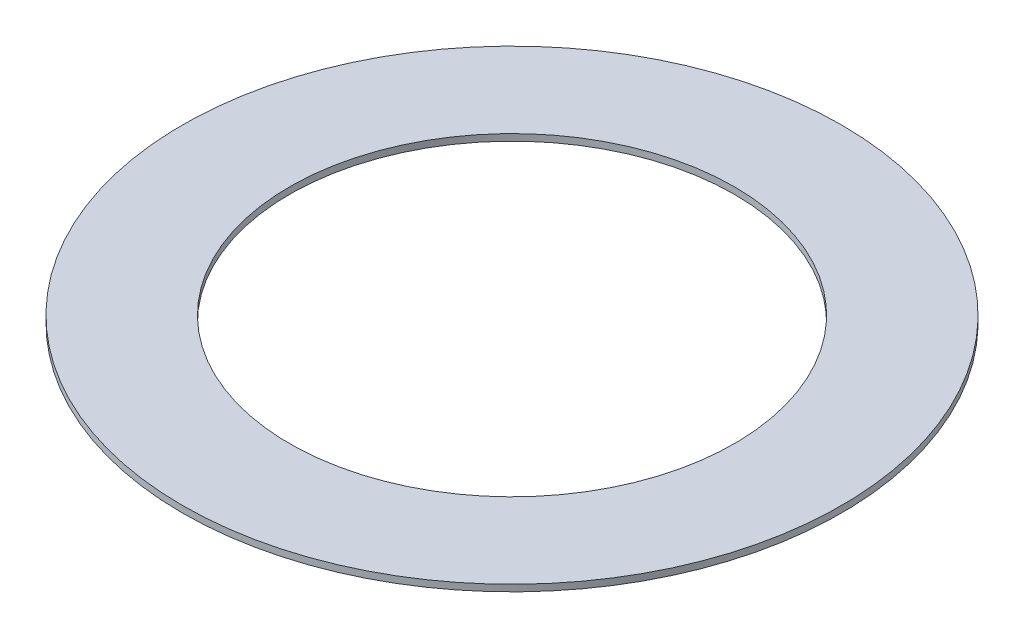
SolidWorks part; units mm, degrees
material "AISI 304"
ref_plane "前视基准面" through (0, 0, 0) normal (0, 0, 1) x (1, 0, 0)
ref_plane "上视基准面" through (0, 0, 0) normal (0, 1, 0) x (1, 0, 0)
ref_plane "右视基准面" through (0, 0, 0) normal (1, 0, 0) x (0, 0, -1)
sketch "草图1" plane through (0, 0, 0) normal (0, 0, 1) x (1, 0, 0)
  line L0 (10, 0.2) -> (6.75, 0.2)
  line L1 (6.75, 0.2) -> (6.75, 0)
  line L2 (6.75, 0) -> (10, 0)
  line L3 (10, 0) -> (10, 0.2)
  line L4 (0, 0.2) -> (0, 0) construction
revolve "旋转1" add sketch "草图1" angle 360 about L4
